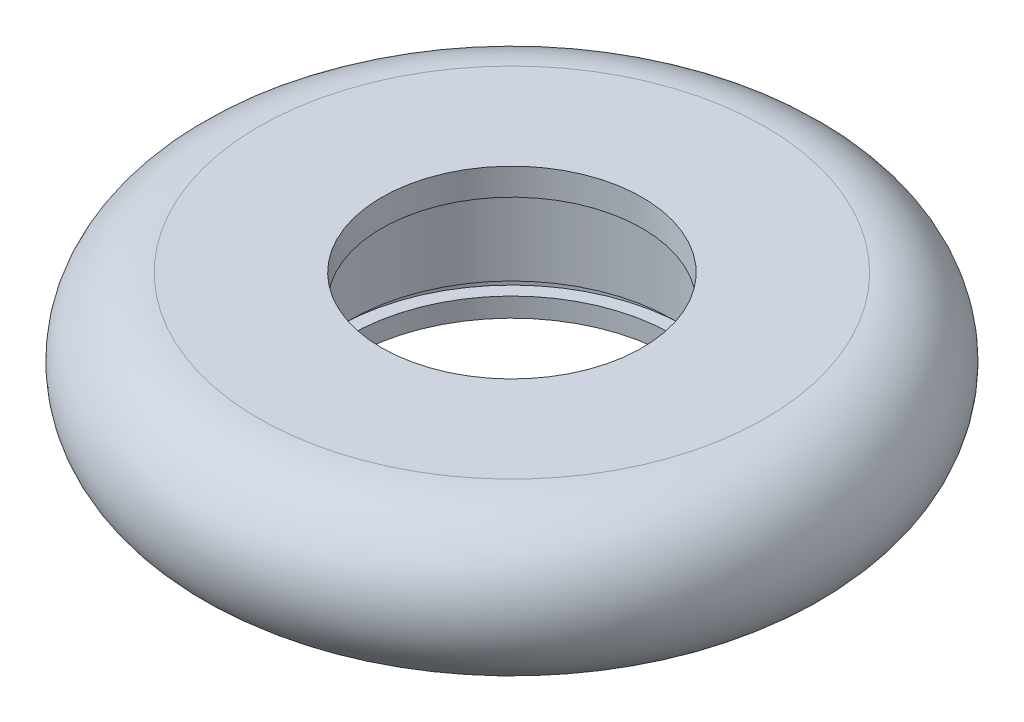
SolidWorks part; units mm, degrees
material "GCr4"
ref_plane "m" through (0, 0, 0) normal (0, 0, 1) x (1, 0, 0)
ref_plane "上视基准面" through (0, 0, 0) normal (0, 1, 0) x (1, 0, 0)
ref_plane "右视基准面" through (0, 0, 0) normal (1, 0, 0) x (0, 0, -1)
sketch "草图1" plane through (0, 0, 0) normal (0, 0, 1) x (1, 0, 0)
  line L0 (0, 0) -> (0, 55.9116) construction
  line L1 (10, 0) -> (33, 0)
  line L6 (33, 20) -> (10, 20)
  line L7 (10, 20) -> (10, 0)
  arc A0 (33, 0) -> (33, 20) centre (33, 10) ccw
  dimension "D2" = 20
  dimension "D1" = 20
  dimension "D3" = 66
  dimension "D4" = 20
revolve "旋转1" add sketch "草图1" angle 360 about L0
ref_plane "基准面2" through (0, 10, 0) normal (0, 1, 0) x (1, 0, 0)
sketch "草图4" plane through (0, 10, 0) normal (0, 1, 0) x (1, 0, 0)
  point P0 (0, 0)
sketch "草图5" plane through (0, 0, 0) normal (0, -1, 0) x (1, 0, 0)
  circle A0 centre (0, 0) radius 21
  dimension "D1" = 42
extrude "切除-拉伸1" cut sketch "草图5" against normal blind 16.5
sketch "草图6" plane through (0, 0, 0) normal (1, 0, 0) x (0, 0, -1)
  line L0 (0, 0) -> (0, 20) construction
  line L1 (10, 20) -> (-10, 20) construction
  line L2 (-21, 16.5) -> (21, 16.5) construction
  line L3 (22.75, 4.2) -> (21, 4.2)
  line L4 (22.75, 4.2) -> (22.75, 2.5)
  line L5 (22.75, 2.5) -> (21, 2.5)
  line L6 (21, 4.2) -> (21, 2.5)
  dimension "D1" = 21
  dimension "D2" = 22.75
  dimension "D3" = 1.7
  dimension "D4" = 12.3
revolve "切除-旋转1" cut sketch "草图6" angle 360 about L0
sketch "草图7" plane through (0, 20, 0) normal (0, 1, 0) x (1, 0, 0)
  circle A0 centre (0, 0) radius 17
  dimension "D1" = 34
extrude "切除-拉伸2" cut sketch "草图7" against normal blind 16
